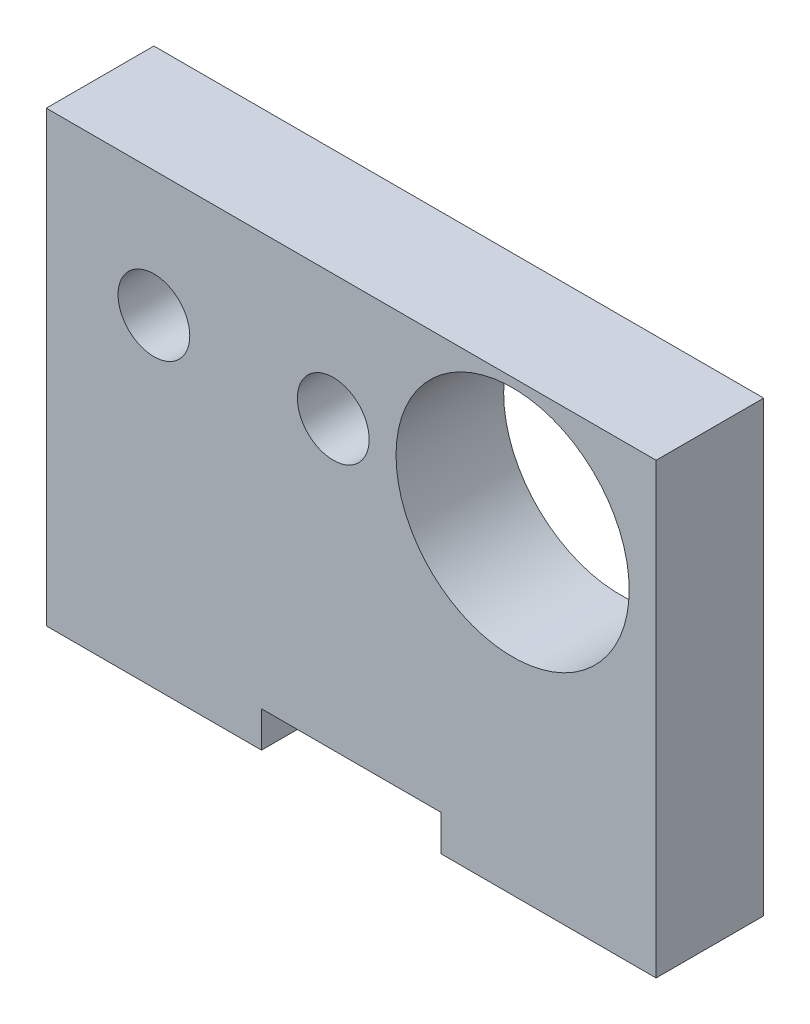
SolidWorks part; units mm, degrees
ref_plane "Plan de face" through (0, 0, 0) normal (0, 0, 1) x (1, 0, 0)
ref_plane "Plan de dessus" through (0, 0, 0) normal (0, 1, 0) x (1, 0, 0)
ref_plane "Plan de droite" through (0, 0, 0) normal (1, 0, 0) x (0, 0, -1)
sketch "Esquisse1" plane through (0, 0, 0) normal (0, 0, 1) x (1, 0, 0)
  line L0 (22, 0) -> (34, 0)
  line L1 (0, 0) -> (12, 0)
  line L2 (0, 0) -> (0, 25)
  line L3 (0, 25) -> (34, 25)
  line L4 (34, 0) -> (34, 25)
  line L6 (12, 0) -> (12, 2)
  line L7 (12, 2) -> (22, 2)
  line L8 (22, 0) -> (22, 2)
  dimension "D1" = 25
  dimension "D2" = 12
  dimension "D3" = 10
  dimension "D4" = 2
  dimension "D5" = 12
extrude "Boss.-Extru.1" add sketch "Esquisse1" along normal blind 6
sketch "Esquisse2" plane through (0, 0, 6) normal (0, 0, 1) x (1, 0, 0)
  line L0 (34, 25) -> (0, 25) construction
  line L2 (0, 25) -> (0, 0) construction
  circle A0 centre (16, 18) radius 2
  circle A1 centre (26, 18) radius 6.5
  circle A2 centre (6, 18) radius 2
  dimension "D1" = 4
  dimension "D2" = 7
  dimension "D3" = 7
  dimension "D4" = 13
  dimension "D5" = 4
  dimension "D6" = 7
  dimension "D7" = 10
  dimension "D9" = 10
  dimension "D8" = 6
extrude "Enlèv. mat.-Extru.1" cut sketch "Esquisse2" against normal through all
